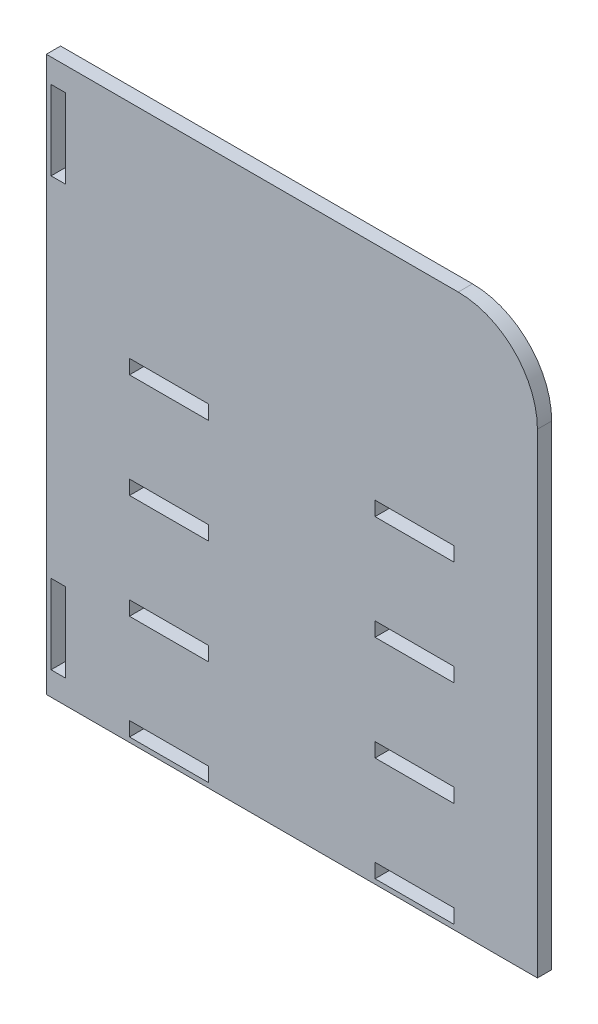
SolidWorks part; units mm, degrees
ref_plane "Front Plane" through (0, 0, 0) normal (0, 0, 1) x (1, 0, 0)
ref_plane "Top Plane" through (0, 0, 0) normal (0, 1, 0) x (1, 0, 0)
ref_plane "Right Plane" through (0, 0, 0) normal (1, 0, 0) x (0, 0, -1)
sketch "Sketch1" plane through (0, 0, 0) normal (0, 0, 1) x (1, 0, 0)
  line L54 (-1817.0569, 752.6923) -> (-1197.0569, 752.6923) construction
  line L55 (-1197.0569, 402.6923) -> (-1817.0569, 402.6923)
  line L56 (-1197.0569, 402.6923) -> (-1197.0569, 1002.6923)
  line L57 (-1297.0569, 1102.6923) -> (-1817.0569, 1102.6923)
  line L58 (-1817.0569, 402.6923) -> (-1817.0569, 1102.6923)
  line L59 (-1811.0569, 1072.6923) -> (-1793.0569, 1072.6923)
  line L60 (-1811.0569, 1072.6923) -> (-1811.0569, 972.6923)
  line L61 (-1811.0569, 972.6923) -> (-1793.0569, 972.6923)
  line L62 (-1793.0569, 1072.6923) -> (-1793.0569, 972.6923)
  line L63 (-1811.0569, 1072.6923) -> (-1793.0569, 972.6923) construction
  line L64 (-1811.0569, 972.6923) -> (-1793.0569, 1072.6923) construction
  line L65 (-1811.0569, 432.6923) -> (-1811.0569, 532.6923)
  line L66 (-1811.0569, 432.6923) -> (-1793.0569, 432.6923)
  line L67 (-1793.0569, 432.6923) -> (-1793.0569, 532.6923)
  line L68 (-1811.0569, 532.6923) -> (-1793.0569, 532.6923)
  line L69 (-1507.0569, 402.6923) -> (-1507.0569, 1102.6923) construction
  line L70 (-1507.0569, 752.6923) -> (-1817.0569, 752.6923)
  line L75 (-1662.0569, 752.6923) -> (-1662.0569, 295.5096) construction
  line L76 (-1302.0569, 408.6923) -> (-1302.0569, 426.6923)
  line L77 (-1712.0569, 408.6923) -> (-1612.0569, 408.6923)
  line L78 (-1712.0569, 408.6923) -> (-1712.0569, 426.6923)
  line L79 (-1712.0569, 426.6923) -> (-1612.0569, 426.6923)
  line L80 (-1612.0569, 408.6923) -> (-1612.0569, 426.6923)
  line L81 (-1712.0569, 408.6923) -> (-1612.0569, 426.6923) construction
  line L82 (-1712.0569, 426.6923) -> (-1612.0569, 408.6923) construction
  line L83 (-1302.0569, 408.6923) -> (-1402.0569, 408.6923)
  line L84 (-1302.0569, 426.6923) -> (-1402.0569, 426.6923)
  line L85 (-1402.0569, 408.6923) -> (-1402.0569, 426.6923)
  line L86 (-1712.0569, 540.6923) -> (-1712.0569, 558.6923)
  line L87 (-1712.0569, 540.6923) -> (-1612.0569, 540.6923)
  line L88 (-1612.0569, 540.6923) -> (-1612.0569, 558.6923)
  line L89 (-1712.0569, 558.6923) -> (-1612.0569, 558.6923)
  line L90 (-1302.0569, 540.6923) -> (-1302.0569, 558.6923)
  line L91 (-1302.0569, 558.6923) -> (-1402.0569, 558.6923)
  line L92 (-1402.0569, 540.6923) -> (-1402.0569, 558.6923)
  line L93 (-1302.0569, 540.6923) -> (-1402.0569, 540.6923)
  line L94 (-1712.0569, 672.6923) -> (-1712.0569, 690.6923)
  line L95 (-1712.0569, 672.6923) -> (-1612.0569, 672.6923)
  line L96 (-1612.0569, 672.6923) -> (-1612.0569, 690.6923)
  line L97 (-1712.0569, 690.6923) -> (-1612.0569, 690.6923)
  line L98 (-1302.0569, 672.6923) -> (-1302.0569, 690.6923)
  line L99 (-1302.0569, 690.6923) -> (-1402.0569, 690.6923)
  line L100 (-1402.0569, 672.6923) -> (-1402.0569, 690.6923)
  line L101 (-1302.0569, 672.6923) -> (-1402.0569, 672.6923)
  line L102 (-1712.0569, 804.6923) -> (-1712.0569, 822.6923)
  line L103 (-1712.0569, 804.6923) -> (-1612.0569, 804.6923)
  line L104 (-1612.0569, 804.6923) -> (-1612.0569, 822.6923)
  line L105 (-1712.0569, 822.6923) -> (-1612.0569, 822.6923)
  line L106 (-1302.0569, 804.6923) -> (-1302.0569, 822.6923)
  line L107 (-1302.0569, 822.6923) -> (-1402.0569, 822.6923)
  line L108 (-1402.0569, 804.6923) -> (-1402.0569, 822.6923)
  line L109 (-1302.0569, 804.6923) -> (-1402.0569, 804.6923)
  arc A1 (-1197.0569, 1002.6923) -> (-1297.0569, 1102.6923) centre (-1297.0569, 1002.6923) ccw
  point P60 (-1802.0569, 1022.6923)
  point P76 (-1662.0569, 417.6923)
  dimension "D17" = 100
  dimension "D3" = 30
  dimension "D15" = 620
  dimension "D18" = 18
  dimension "D19" = 100
  dimension "D20" = 6
  dimension "D21" = 30
  dimension "D22" = 6
  dimension "D23" = 18
  dimension "D24" = 100
  dimension "D26" = 4
extrude "Boss-Extrude2" add sketch "Sketch1" along normal blind 18
